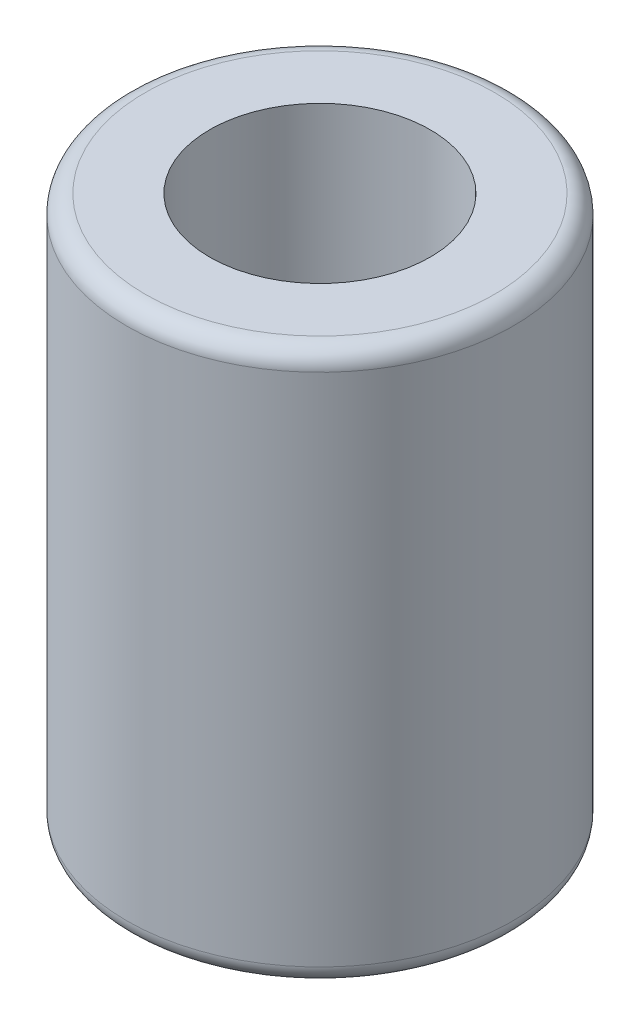
SolidWorks part; units mm, degrees
material "Chrome Stainless Steel"
ref_plane "Front Plane" through (0, 0, 0) normal (0, 0, 1) x (1, 0, 0)
ref_plane "Top Plane" through (0, 0, 0) normal (0, 1, 0) x (1, 0, 0)
ref_plane "Right Plane" through (0, 0, 0) normal (1, 0, 0) x (0, 0, -1)
sketch "Sketch1" plane through (0, 0, 0) normal (0, 1, 0) x (1, 0, 0)
  circle A0 centre (0, 0) radius 10.5
  circle A1 centre (0, 0) radius 6
  dimension "D1" = 12
  dimension "D2" = 21
extrude "Boss-Extrude1" add sketch "Sketch1" along normal blind 30
fillet "Fillet1" radius 1 2 edges at (0, 0, 10.5) (0, 30, 10.5)
